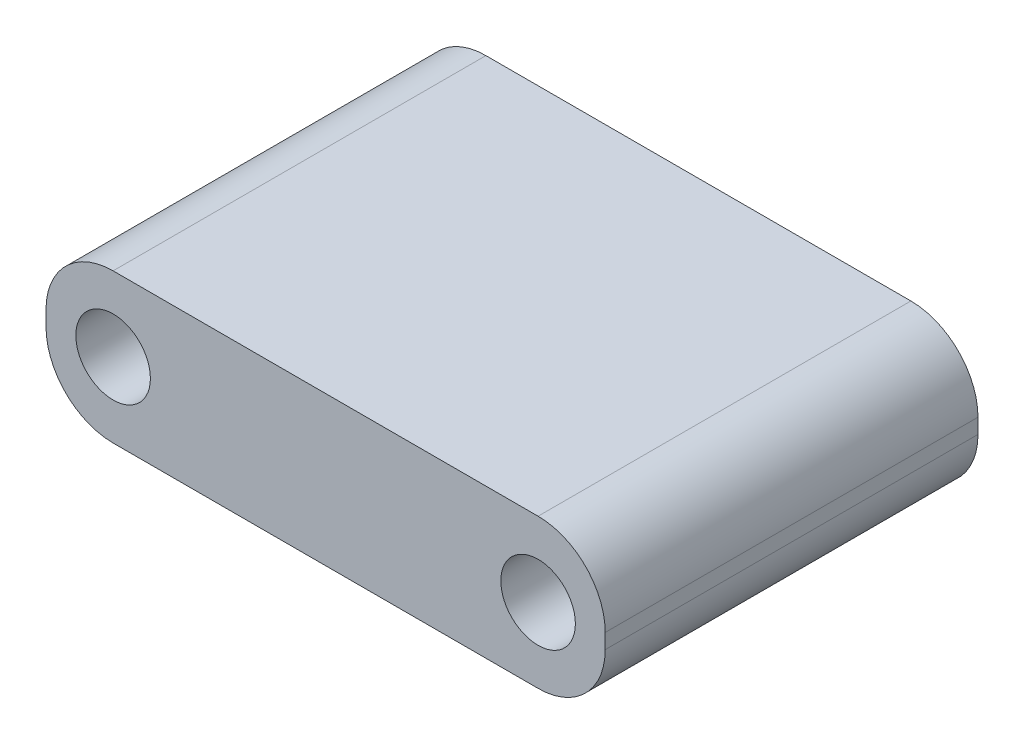
SolidWorks part; units mm, degrees
ref_plane "Front Plane" through (0, 0, 0) normal (0, 0, 1) x (1, 0, 0)
ref_plane "Top Plane" through (0, 0, 0) normal (0, 1, 0) x (1, 0, 0)
ref_plane "Right Plane" through (0, 0, 0) normal (1, 0, 0) x (0, 0, -1)
sketch "Sketch1" plane through (0, 0, 0) normal (0, 0, 1) x (1, 0, 0)
  line L1 (-61.4374, 527.6156) -> (-50.0374, 527.6156)
  line L2 (-63.2374, 525.8156) -> (-63.2374, 525.4156)
  line L3 (-61.4374, 523.6156) -> (-50.0374, 523.6156)
  line L4 (-48.2374, 525.8156) -> (-48.2374, 525.4156)
  arc A0 (-61.4374, 527.6156) -> (-63.2374, 525.8156) centre (-61.4374, 525.8156) ccw
  arc A1 (-50.0374, 523.6156) -> (-48.2374, 525.4156) centre (-50.0374, 525.4156) ccw
  arc A2 (-50.0374, 527.6156) -> (-48.2374, 525.8156) centre (-50.0374, 525.8156) cw
  arc A3 (-63.2374, 525.4156) -> (-61.4374, 523.6156) centre (-61.4374, 525.4156) ccw
  circle A4 centre (-61.4374, 525.6156) radius 1
  circle A5 centre (-50.0374, 525.6156) radius 1
  point P6 (-63.2374, 527.6156)
  point P11 (-48.2374, 527.6156)
  dimension "D3" = 1.8
  dimension "D1" = 4
  dimension "D2" = 15
extrude "Boss-Extrude1" add sketch "Sketch1" along normal blind 10
